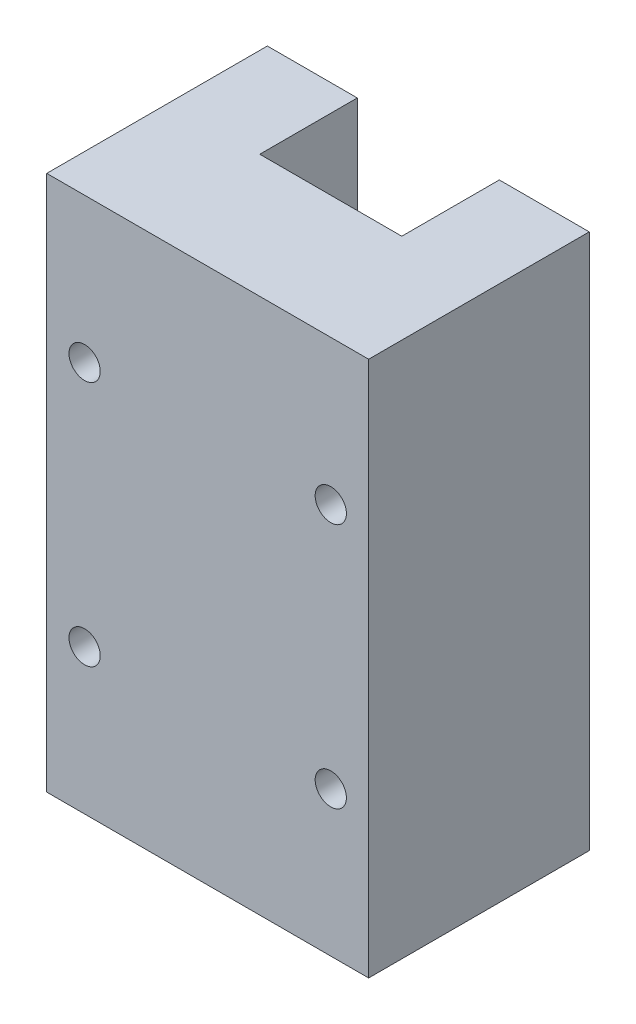
SolidWorks part; units mm, degrees
ref_plane "前视基准面" through (0, 0, 0) normal (0, 0, 1) x (1, 0, 0)
ref_plane "上视基准面" through (0, 0, 0) normal (0, 1, 0) x (1, 0, 0)
ref_plane "右视基准面" through (0, 0, 0) normal (1, 0, 0) x (0, 0, -1)
sketch "草图1" plane through (0, 0, 0) normal (0, 1, 0) x (1, 0, 0)
  line L1 (-17, 23.3) -> (17, 23.3)
  line L2 (-17, 23.3) -> (-17, 0)
  line L3 (-17, 0) -> (17, 0)
  line L4 (17, 23.3) -> (17, 0)
  dimension "D1" = 34
  dimension "D2" = 23.3
extrude "凸台-拉伸1" add sketch "草图1" along normal mid plane 56.6
sketch "草图2" plane through (0, 28.3, 0) normal (0, 1, 0) x (1, 0, 0)
  line L0 (17, 23.3) -> (-17, 23.3) construction
  line L1 (-7.5, 23.3) -> (7.5, 23.3)
  line L2 (-7.5, 23.3) -> (-7.5, 13)
  line L3 (-7.5, 13) -> (7.5, 13)
  line L4 (7.5, 23.3) -> (7.5, 13)
  line L5 (0, 0) -> (0, 26.902) construction
  line L6 (-17, 0) -> (17, 0) construction
  dimension "D1" = 15
  dimension "D2" = 13
extrude "切除-拉伸1" cut sketch "草图2" against normal through all
hole_wizard "M4x0.7 螺纹孔1" positions "草图4" profile "草图3" tap size "M4x0.7" standard "JIS"
sketch "草图4" plane through (0, 0, 0) normal (0, 0, 1) x (1, 0, 0)
  line L0 (0, 0) -> (0, 26.7502) construction
  line L2 (0, 0) -> (-25.7671, 0) construction
  point P1 (-13, 13)
  point P14 (-13, -13)
  point P15 (13, -13)
  point P16 (13, 13)
  dimension "D1" = 26
  dimension "D2" = 26
sketch "草图3" plane through (-13, 13, 0) normal (1, 0, 0) x (0, -1, 0)
  line L0 (0, 0) -> (0, 11.0914)
  line L1 (0, 11.0914) -> (1.65, 10.1)
  line L2 (1.65, 10.1) -> (1.65, 0)
  line L5 (1.65, 0) -> (0, 0)
  line L10 (0, 11.0914) -> (-1.65, 10.1) construction
  line L11 (0, -6.35) -> (0, 107.95) construction
  dimension "螺纹孔钻头直径" = 3.3
  dimension "螺纹孔钻头深度" = 10.1
  dimension "导头角度" = 118
cosmetic thread "孔螺蚊线1" parameters "D1"=8, "D2"=4
cosmetic thread "孔螺蚊线2" parameters "D1"=8, "D2"=4
cosmetic thread "孔螺蚊线3" parameters "D1"=8, "D2"=4
cosmetic thread "孔螺蚊线4" parameters "D1"=8, "D2"=4
